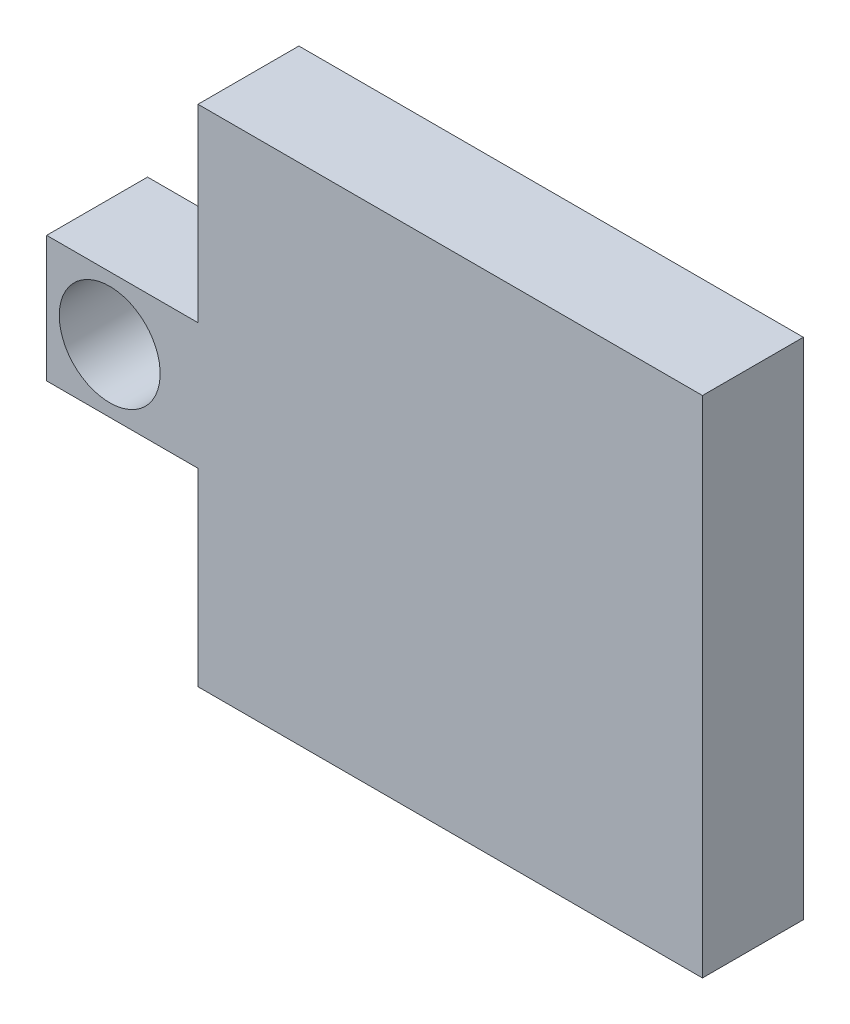
SolidWorks part; units mm, degrees
ref_plane "Front Plane" through (0, 0, 0) normal (0, 0, 1) x (1, 0, 0)
ref_plane "Top Plane" through (0, 0, 0) normal (0, 1, 0) x (1, 0, 0)
ref_plane "Right Plane" through (0, 0, 0) normal (1, 0, 0) x (0, 0, -1)
sketch "Sketch1" plane through (0, 0, 0) normal (0, 0, 1) x (1, 0, 0)
  line L1 (-25, -25) -> (25, -25)
  line L2 (-25, -25) -> (-25, 25)
  line L3 (-25, 25) -> (25, 25)
  line L4 (25, -25) -> (25, 25)
  line L5 (-25, -25) -> (25, 25) construction
  line L6 (-25, 25) -> (25, -25) construction
  point P0 (0, 0)
  dimension "D1" = 50
extrude "Boss-Extrude1" add sketch "Sketch1" along normal blind 10
sketch "Sketch6" plane through (-25, 0, 0) normal (-1, 0, 0) x (0, 0, 1)
  line L1 (10, -6.25) -> (0, -6.25)
  line L2 (10, -6.25) -> (10, 6.25)
  line L3 (10, 6.25) -> (0, 6.25)
  line L4 (0, -6.25) -> (0, 6.25)
  line L5 (10, -6.25) -> (0, 6.25) construction
  line L6 (10, 6.25) -> (0, -6.25) construction
  line L7 (0, 25) -> (0, -25) construction
  line L8 (10, 25) -> (10, -25) construction
  point P0 (5, 0)
  dimension "D2" = 12.5
extrude "Boss-Extrude5" add sketch "Sketch6" along normal blind 15
sketch "Sketch7" plane through (0, 0, 0) normal (0, 0, -1) x (-1, 0, 0)
  line L0 (40, 6.25) -> (40, -6.25) construction
  circle A0 centre (33.75, 0) radius 5
  dimension "D1" = 10
  dimension "D2" = 6.25
extrude "Cut-Extrude2" cut sketch "Sketch7" against normal through all
sketch "Sketch14" plane through (0, 0, 0) normal (0, 0, -1) x (-1, 0, 0)
  circle A0 centre (33.75, 0) radius 5 construction
  circle A1 centre (33.75, 0) radius 5
curve "Helix/Spiral1" pitch 5 height 10 turns 2
